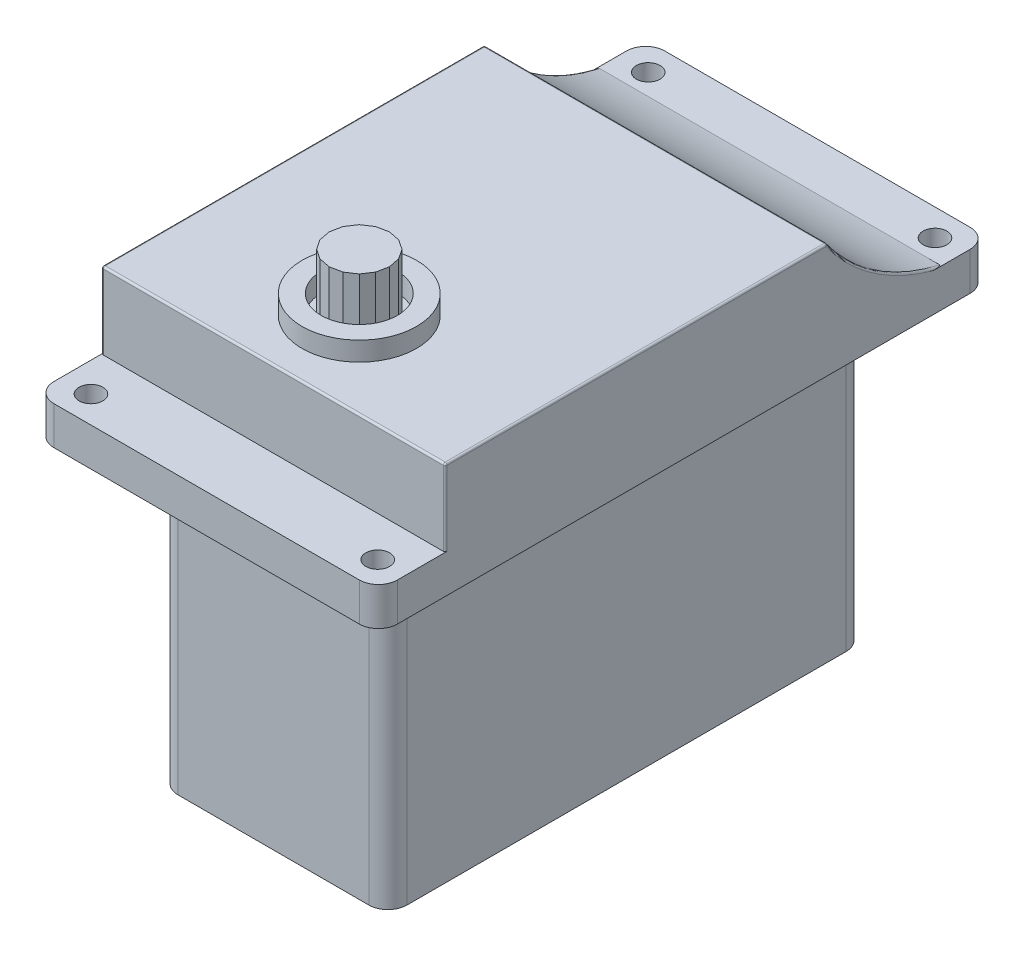
SolidWorks part; units mm, degrees
ref_plane "Front Plane" through (0, 0, 0) normal (0, 0, 1) x (1, 0, 0)
ref_plane "Top Plane" through (0, 0, 0) normal (0, 1, 0) x (1, 0, 0)
ref_plane "Right Plane" through (0, 0, 0) normal (1, 0, 0) x (0, 0, -1)
sketch "Sketch1" plane through (0, 0, 0) normal (0, 1, 0) x (1, 0, 0)
  line L1 (-5, 12.5) -> (5, 12.5)
  line L2 (-6, 11.5) -> (-6, -11.5)
  line L3 (-5, -12.5) -> (5, -12.5)
  line L4 (6, 11.5) -> (6, -11.5)
  line L5 (-6, 12.5) -> (6, -12.5) construction
  line L6 (-6, -12.5) -> (6, 12.5) construction
  arc A0 (5, -12.5) -> (6, -11.5) centre (5, -11.5) ccw
  arc A1 (-6, -11.5) -> (-5, -12.5) centre (-5, -11.5) ccw
  arc A2 (5, 12.5) -> (6, 11.5) centre (5, 11.5) cw
  arc A3 (-5, 12.5) -> (-6, 11.5) centre (-5, 11.5) ccw
  point P0 (0, 0)
  dimension "D3" = 1
  dimension "D1" = 25
  dimension "D2" = 12
extrude "Boss-Extrude1" add sketch "Sketch1" along normal blind 16
sketch "Sketch2" plane through (0, 16, 0) normal (0, 1, 0) x (1, 0, 0)
  line L1 (-8, 16) -> (8, 16)
  line L2 (-9, 15) -> (-9, -15)
  line L3 (-8, -16) -> (8, -16)
  line L4 (9, 15) -> (9, -15)
  line L5 (-9, 16) -> (9, -16) construction
  line L6 (-9, -16) -> (9, 16) construction
  arc A0 (8, -16) -> (9, -15) centre (8, -15) ccw
  arc A1 (-9, -15) -> (-8, -16) centre (-8, -15) ccw
  arc A2 (8, 16) -> (9, 15) centre (8, 15) cw
  arc A3 (-8, 16) -> (-9, 15) centre (-8, 15) ccw
  point P0 (0, 0)
  dimension "D3" = 1
  dimension "D1" = 32
  dimension "D2" = 18
extrude "Boss-Extrude2" add sketch "Sketch2" along normal blind 2
sketch "Sketch4" plane through (0, 0, 0) normal (1, 0, 0) x (0, 0, -1)
  line L0 (-15, 18) -> (15, 18) construction
  line L1 (-12.5, 18) -> (13.5, 18)
  line L2 (-12.5, 18) -> (-12.5, 22)
  line L3 (-12.5, 22) -> (7.5, 22)
  line L4 (-12.5, 16) -> (-12.5, 0) construction
  arc A0 (13.5, 18) -> (7.5, 22) centre (15.6739, 27.7608) cw
  point P9 (11.6559, 22)
  point P10 (14.1383, 18)
  dimension "D3" = 10
  dimension "D1" = 4
  dimension "D2" = 20
  dimension "D4" = 6
extrude "Boss-Extrude3" add sketch "Sketch4" along normal mid plane 18
sketch "Sketch5" plane through (0, 18, 0) normal (0, 1, 0) x (1, 0, 0)
  circle A0 centre (-7.4608, -14.595) radius 0.6228
  circle A1 centre (7.5612, -14.595) radius 0.6228
  circle A2 centre (-7.4608, 14.5972) radius 0.6228
  circle A3 centre (7.5612, 14.5972) radius 0.6228
  point P8 (7.6883, 14.5972)
  point P9 (-7.4608, -14.5125)
  point P10 (7.5612, -14.595)
extrude "Cut-Extrude1" cut sketch "Sketch5" against normal blind 18
fillet "Fillet1" radius 0.1 8 edges at (0, 22, -7.5) (-9, 22, 2.5) (9, 22, 2.5) (0, 22, 12.5) (-9, 20, 12.5) (9, 20, 12.5) (-9, 19.4403, -10.1269) (9, 19.4403, -10.1269)
sketch "Sketch6" plane through (0, 22, 0) normal (0, 1, 0) x (1, 0, 0)
  line L0 (0, 0) -> (0, -8) construction
  circle A0 centre (0, -8) radius 2
  circle A1 centre (0, -8) radius 3
  point P4 (0, -10.0442)
  dimension "D2" = 4
  dimension "D1" = 8
  dimension "D3" = 1
extrude "Boss-Extrude4" add sketch "Sketch6" along normal blind 1
sketch "Sketch7" plane through (0, 22, 0) normal (0, 1, 0) x (1, 0, 0)
  line L0 (-1.1178, -6.8822) -> (-1.4605, -7.395)
  line L1 (1.5809, -8) -> (1.4605, -7.395)
  line L2 (1.4605, -7.395) -> (1.1178, -6.8822)
  line L3 (1.1178, -6.8822) -> (0.605, -6.5395)
  line L4 (0.605, -6.5395) -> (0, -6.4191)
  line L5 (0, -6.4191) -> (-0.605, -6.5395)
  line L6 (-0.605, -6.5395) -> (-1.1178, -6.8822)
  line L7 (-1.4605, -7.395) -> (-1.5809, -8)
  line L8 (-1.5809, -8) -> (-1.4605, -8.605)
  line L9 (-1.4605, -8.605) -> (-1.1178, -9.1178)
  line L10 (-1.1178, -9.1178) -> (-0.605, -9.4605)
  line L11 (-0.605, -9.4605) -> (0, -9.5809)
  line L12 (0, -9.5809) -> (0.605, -9.4605)
  line L13 (0.605, -9.4605) -> (1.1178, -9.1178)
  line L14 (1.1178, -9.1178) -> (1.4605, -8.605)
  line L15 (1.4605, -8.605) -> (1.5809, -8)
  circle A0 centre (0, -8) radius 1.5505 construction
extrude "Boss-Extrude5" add sketch "Sketch7" along normal blind 3
